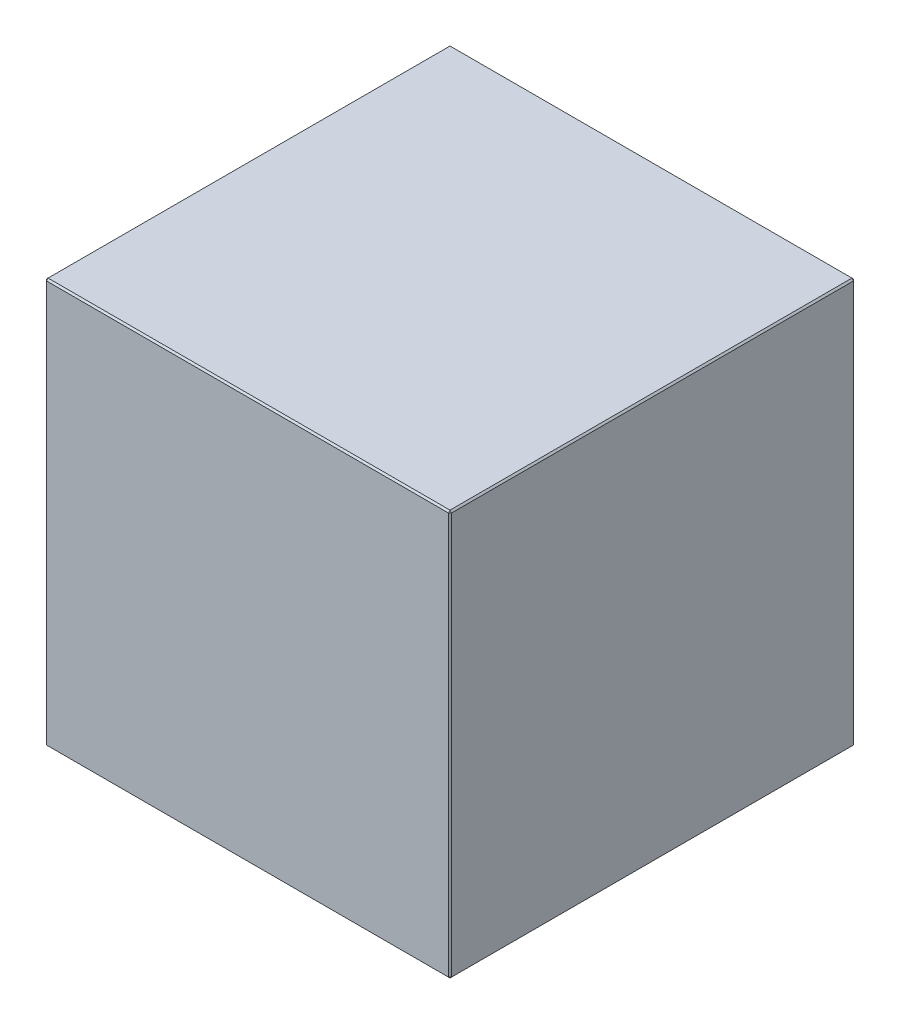
SolidWorks part; units mm, degrees
ref_plane "前视基准面" through (0, 0, 0) normal (0, 0, 1) x (1, 0, 0)
ref_plane "上视基准面" through (0, 0, 0) normal (0, 1, 0) x (1, 0, 0)
ref_plane "右视基准面" through (0, 0, 0) normal (1, 0, 0) x (0, 0, -1)
sketch "草图1" plane through (0, 0, 0) normal (0, 1, 0) x (1, 0, 0)
  line L1 (-125, -125) -> (125, -125)
  line L2 (-125, -125) -> (-125, 125)
  line L3 (-125, 125) -> (125, 125)
  line L4 (125, -125) -> (125, 125)
  line L5 (-125, -125) -> (125, 125) construction
  line L6 (-125, 125) -> (125, -125) construction
  point P0 (0, 0)
  dimension "D1" = 250
  dimension "D2" = 250
extrude "凸台-拉伸1" add sketch "草图1" along normal blind 250
chamfer "倒角1" distance 1 angle 45 12 edges at (-125, 0, 0) (-125, 125, -125) (0, 0, -125) (-125, 250, 0) (0, 250, -125) (125, 250, 0) (125, 125, -125) (125, 0, 0) (-125, 125, 125) (0, 250, 125) (125, 125, 125) (0, 0, 125)
